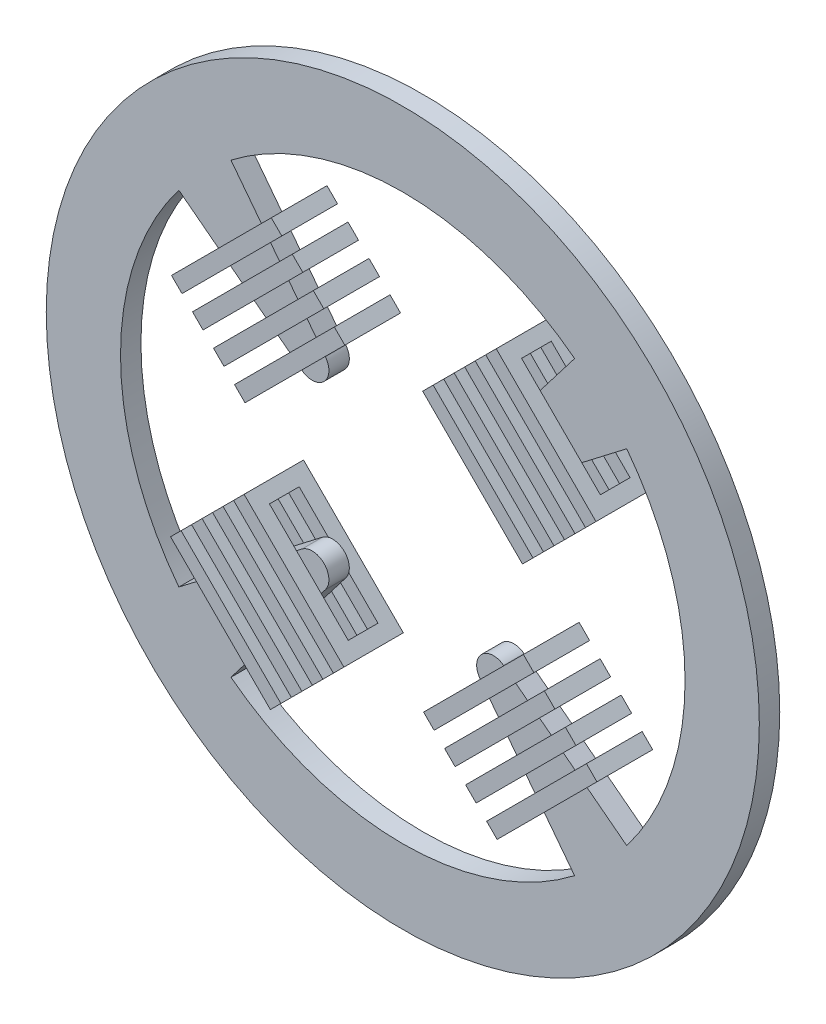
SolidWorks part; units mm, degrees
other "標示1"
sketch "草圖65"
ref_plane "前基準面" through (0, 0, 0) normal (0, 0, 1) x (1, 0, 0)
ref_plane "上基準面" through (0, 0, 0) normal (0, 1, 0) x (1, 0, 0)
ref_plane "右基準面" through (0, 0, 0) normal (1, 0, 0) x (0, 0, -1)
sketch "草圖1" plane through (0, 0, 0) normal (0, 0, 1) x (1, 0, 0)
  circle A0 centre (0, 0) radius 0.96
  circle A1 centre (0, 0) radius 0.76
extrude "填料-伸長1" add sketch "草圖1" along normal blind 0.055
sketch "草圖2" plane through (0, 0, 0.055) normal (0, 0, 1) x (1, 0, 0)
  line L0 (0, 0) -> (0, 1.565) construction
  line L1 (0, 0) -> (-1.8584, 0) construction
  line L2 (-0.0447, 0.3392) -> (-0.0992, 0.7535)
  line L3 (0.0447, 0.3392) -> (0.0992, 0.7535)
  line L4 (0.2714, 0.2082) -> (0.6029, 0.4627)
  line L5 (0.2082, 0.2714) -> (0.4627, 0.6029)
  line L6 (0.2082, -0.2714) -> (0.4627, -0.6029)
  line L7 (0.2714, -0.2082) -> (0.6029, -0.4627)
  line L8 (-0.2714, -0.2082) -> (-0.6029, -0.4627)
  line L9 (-0.2082, -0.2714) -> (-0.4627, -0.6029)
  line L10 (-0.2082, 0.2714) -> (-0.4627, 0.6029)
  line L11 (-0.2714, 0.2082) -> (-0.6029, 0.4627)
  circle A0 centre (0, 0) radius 0.3
  circle A1 centre (0, 0) radius 0.76 construction
  arc A3 (-0.0447, 0.3392) -> (0.0447, 0.3392) centre (0, 0.345) ccw
  arc A4 (0.0992, 0.7535) -> (-0.0992, 0.7535) centre (0, 0) ccw
  arc A5 (-0.76, 0) -> (0.76, 0) centre (0, 0) ccw
  arc A6 (0.6029, 0.4627) -> (0.4627, 0.6029) centre (0, 0) ccw
  arc A7 (0.2082, 0.2714) -> (0.2714, 0.2082) centre (0.244, 0.244) ccw
  arc A8 (0.4627, -0.6029) -> (0.6029, -0.4627) centre (0, 0) ccw
  arc A9 (0.2714, -0.2082) -> (0.2082, -0.2714) centre (0.244, -0.244) ccw
  arc A10 (-0.6029, -0.4627) -> (-0.4627, -0.6029) centre (0, 0) ccw
  arc A11 (-0.2082, -0.2714) -> (-0.2714, -0.2082) centre (-0.244, -0.244) ccw
  arc A12 (-0.4627, 0.6029) -> (-0.6029, 0.4627) centre (0, 0) ccw
  arc A13 (-0.2714, 0.2082) -> (-0.2082, 0.2714) centre (-0.244, 0.244) ccw
  point P23 (0, 0)
  point P34 (0, 0)
  point P41 (0, 0)
  circle M4 centre (0, 0) radius 0.76
  dimension "D1" = 7.5
  dimension "D3" = 2
  dimension "D4" = 4
  dimension "D2" = 7.5
extrude "填料-伸長2" add sketch "草圖2" against normal blind 0.055 contours L11 A13 L10 M4 | L5 A7 L4 M4 | L7 A9 L6 M4 | A11 L8 L9 M4
sketch "草圖7" plane through (0, 0, 0.055) normal (0, 0, 1) x (1, 0, 0)
  line L0 (0.2121, 0.2121) -> (0.2404, 0.2404) construction
  line L1 (0.2404, 0.2404) -> (0.2013, 0.2795) construction
  line L2 (0.2404, 0.2404) -> (0.5894, 0.5894) construction
  line L3 (0.0244, -0.0244) -> (-0.6648, 0.6648) construction
  line L4 (0.2404, -0.2404) -> (0.3328, -0.148)
  arc A0 (0.2082, 0.2714) -> (0.2714, 0.2082) centre (0.244, 0.244) ccw construction
  arc A1 (-0.2082, -0.2714) -> (-0.2714, -0.2082) centre (-0.244, -0.244) ccw construction
  arc A2 (-0.2714, 0.2082) -> (-0.2082, 0.2714) centre (-0.244, 0.244) ccw construction
  arc A3 (0.2714, -0.2082) -> (0.2082, -0.2714) centre (0.244, -0.244) ccw construction
  point P5 (0.297, 0.297)
  point P7 (-0.2121, -0.2121)
  point P8 (0.3536, 0.3536)
  point P9 (0.4101, 0.4101)
  point P12 (-0.2404, -0.2404)
  point P16 (-0.297, -0.297)
  point P17 (-0.3536, -0.3536)
  point P18 (-0.4101, -0.4101)
  point P20 (0.2404, -0.2404)
  point P23 (-0.2404, 0.2404)
  point P24 (-0.2121, 0.2121)
  point P25 (0.2121, -0.2121)
  point P29 (0.297, -0.297)
  point P33 (0.3536, -0.3536)
  point P34 (0.4101, -0.4101)
  point P35 (-0.297, 0.297)
  point P36 (-0.3536, 0.3536)
  point P37 (-0.4101, 0.4101)
  point P40 (0.4667, -0.4667)
  point P41 (0.5233, -0.5233)
  point P42 (0.4667, 0.4667)
  point P43 (0.5233, 0.5233)
  point P44 (-0.4667, 0.4667)
  point P45 (-0.5233, 0.5233)
  point P46 (-0.4667, -0.4667)
  point P47 (-0.5233, -0.5233)
  point P48 (0, 0)
  dimension "D1" = 0.08
  dimension "D2" = 0.08
  dimension "D3" = 0.08
  dimension "D4" = 0.04
  dimension "D5" = 0.04
  dimension "D6" = 0.08
  dimension "D7" = 0.08
  dimension "D8" = 0.08
  dimension "D9" = 0.04
  dimension "D10" = 0.04
  dimension "D11" = 0.08
  dimension "D12" = 0.08
  dimension "D13" = 0.08
  dimension "D14" = 0.08
  dimension "D15" = 0.08
  dimension "D16" = 0.08
  dimension "D17" = 0.08
  dimension "D18" = 0.08
  dimension "D19" = 0.08
  dimension "D20" = 0.08
  dimension "D21" = 0.08
  dimension "D22" = 0.08
  dimension "D23" = 0.08
  dimension "D24" = 0.08
ref_plane "平面5" through (0.2404, 0.2404, 0) normal (0.7071, 0.7071, 0) x (-0.7071, 0.7071, 0)
sketch "草圖11" plane through (0.2404, 0.2404, 0) normal (0.7071, 0.7071, 0) x (-0.7071, 0.7071, 0)
  line L0 (0, 0.055) -> (0, 0.1261) construction
  line L1 (-0.15, 0.0675) -> (0.15, 0.0675)
  line L2 (0.19, 0.1075) -> (-0.19, 0.1075)
  line L7 (-0.19, -0.0525) -> (0.19, -0.0525)
  line L17 (0.19, 0.1075) -> (0.19, -0.0525)
  line L18 (-0.19, 0.1075) -> (-0.19, -0.0525)
  line L19 (-0.15, -0.0125) -> (0.15, -0.0125)
  line L20 (-0.15, 0.0675) -> (-0.15, -0.0125)
  line L21 (0.15, 0.0675) -> (0.15, -0.0125)
  point P1 (0, 0.0275)
  point P2 (0, -0.0125)
  point P9 (0, 0.055)
  point P10 (0, -0.0525)
  point P11 (0, 0)
  point P13 (0, 0.1075)
  point P16 (0, -0.0525)
  point P19 (0, 0.0675)
  point P21 (0, 0.0675)
  point P22 (0, 0.1075)
  point P24 (0, -0.0125)
  dimension "D1" = 0.04
  dimension "D2" = 0.04
  dimension "D3" = 0.38
  dimension "D4" = 0.04
  dimension "D7" = 0.04
extrude "填料-伸長3" add sketch "草圖11" along normal blind 0.04 separate body
ref_plane "平面6" through (0.297, 0.297, 0) normal (0.7071, 0.7071, 0) x (0.7071, -0.7071, 0)
ref_plane "平面7" through (0.3536, 0.3536, 0) normal (0.7071, 0.7071, 0) x (0.7071, -0.7071, 0)
ref_plane "平面8" through (0.4101, 0.4101, 0) normal (0.7071, 0.7071, 0) x (0.7071, -0.7071, 0)
ref_plane "平面9" through (-0.2404, -0.2404, 0) normal (0.7071, 0.7071, 0) x (0.7071, -0.7071, 0)
ref_plane "平面10" through (-0.297, -0.297, 0) normal (0.7071, 0.7071, 0) x (0.7071, -0.7071, 0)
ref_plane "平面11" through (-0.3536, -0.3536, 0) normal (0.7071, 0.7071, 0) x (0.7071, -0.7071, 0)
ref_plane "平面12" through (-0.4101, -0.4101, 0) normal (0.7071, 0.7071, 0) x (0.7071, -0.7071, 0)
ref_plane "平面13" through (0.2404, -0.2404, 0) normal (0.7071, -0.7071, 0) x (0.7071, 0.7071, 0)
ref_plane "平面14" through (0.297, -0.297, 0) normal (0.7071, -0.7071, 0) x (0, 0, -1)
ref_plane "平面15" through (0.3536, -0.3536, 0) normal (0.7071, -0.7071, 0) x (0, 0, -1)
ref_plane "平面16" through (0.4101, -0.4101, 0) normal (0.7071, -0.7071, 0) x (0, 0, -1)
ref_plane "平面17" through (-0.2404, 0.2404, 0) normal (0.7071, -0.7071, 0) x (0, 0, -1)
ref_plane "平面18" through (-0.297, 0.297, 0) normal (0.7071, -0.7071, 0) x (0, 0, -1)
ref_plane "平面19" through (-0.3536, 0.3536, 0) normal (0.7071, -0.7071, 0) x (0, 0, -1)
ref_plane "平面20" through (-0.4101, 0.4101, 0) normal (0.7071, -0.7071, 0) x (0, 0, -1)
sketch "草圖60" plane through (0.2404, -0.2404, 0) normal (0.7071, -0.7071, 0) x (0.7071, 0.7071, 0)
sketch "草圖62" plane through (0.2404, -0.2404, 0) normal (0.7071, -0.7071, 0) x (0.7071, 0.7071, 0)
  line L0 (0, -0.0586) -> (0, 0.1686)
  line L2 (0.15, 0.065) -> (-0.15, 0.065)
  line L3 (-0.15, 0.065) -> (-0.15, -0.005)
  line L4 (-0.15, -0.005) -> (0.15, -0.005)
  line L5 (0.15, -0.005) -> (0.15, 0.065)
  line L6 (0.19, 0.105) -> (-0.19, 0.105)
  line L7 (-0.19, 0.105) -> (-0.19, -0.045)
  line L8 (-0.19, -0.045) -> (0.19, -0.045)
  line L9 (0.19, -0.045) -> (0.19, 0.105)
  point P0 (0, 0.065)
  point P4 (0, 0.055)
  point P5 (0, -0.005)
  point P8 (0, 0.105)
  point P11 (0, 0.065)
  point P14 (0, -0.045)
  point P18 (0, 0.105)
  dimension "D1" = 0.01
  dimension "D2" = 0.06
  dimension "D3" = 0.04
  dimension "D4" = 0.04
  dimension "D5" = 0.38
  dimension "D6" = 0.3
sketch "草圖64" plane through (0.297, -0.297, 0) normal (0.7071, -0.7071, 0) x (0, 0, -1)
  line L0 (0.045, 0.19) -> (-0.105, 0.19) construction
  line L1 (0.005, 0.15) -> (-0.065, 0.15) construction
  line L2 (0.045, -0.19) -> (0.045, 0.19) construction
  line L3 (0.005, -0.15) -> (0.005, 0.15) construction
  line L4 (-0.065, -0.15) -> (0.005, -0.15) construction
  line L5 (-0.065, 0.15) -> (-0.065, -0.15) construction
  line L6 (-0.105, -0.19) -> (0.045, -0.19) construction
  line L7 (-0.105, 0.19) -> (-0.105, -0.19) construction
  line L8 (0.045, 0.19) -> (-0.105, 0.19)
  line L9 (0.005, 0.15) -> (-0.065, 0.15)
  line L10 (0.045, -0.19) -> (0.045, 0.19)
  line L11 (0.005, -0.15) -> (0.005, 0.15)
  line L12 (-0.065, -0.15) -> (0.005, -0.15)
  line L13 (-0.065, 0.15) -> (-0.065, -0.15)
  line L14 (-0.105, -0.19) -> (0.045, -0.19)
  line L15 (-0.105, 0.19) -> (-0.105, -0.19)
sketch "草圖68" plane through (0.3536, -0.3536, 0) normal (0.7071, -0.7071, 0) x (0, 0, -1)
  line L0 (-0.105, -0.19) -> (0.045, -0.19) construction
  line L1 (-0.065, -0.15) -> (0.005, -0.15) construction
  line L2 (0.005, -0.15) -> (0.005, 0.15) construction
  line L3 (-0.065, 0.15) -> (-0.065, -0.15) construction
  line L4 (0.005, 0.15) -> (-0.065, 0.15) construction
  line L5 (0.045, -0.19) -> (0.045, 0.19) construction
  line L6 (0.045, 0.19) -> (-0.105, 0.19) construction
  line L7 (-0.105, 0.19) -> (-0.105, -0.19) construction
  line L8 (-0.105, -0.19) -> (0.045, -0.19)
  line L9 (-0.065, -0.15) -> (0.005, -0.15)
  line L10 (0.005, -0.15) -> (0.005, 0.15)
  line L11 (-0.065, 0.15) -> (-0.065, -0.15)
  line L12 (0.005, 0.15) -> (-0.065, 0.15)
  line L13 (0.045, -0.19) -> (0.045, 0.19)
  line L14 (0.045, 0.19) -> (-0.105, 0.19)
  line L15 (-0.105, 0.19) -> (-0.105, -0.19)
sketch "草圖69" plane through (0.4101, -0.4101, 0) normal (0.7071, -0.7071, 0) x (0, 0, -1)
  line L0 (0.045, -0.19) -> (0.045, 0.19) construction
  line L1 (0.045, 0.19) -> (-0.105, 0.19) construction
  line L2 (-0.105, 0.19) -> (-0.105, -0.19) construction
  line L3 (-0.105, -0.19) -> (0.045, -0.19) construction
  line L4 (-0.065, -0.15) -> (0.005, -0.15) construction
  line L5 (0.005, -0.15) -> (0.005, 0.15) construction
  line L6 (-0.065, 0.15) -> (-0.065, -0.15) construction
  line L7 (0.005, 0.15) -> (-0.065, 0.15) construction
  line L8 (0.045, -0.19) -> (0.045, 0.19)
  line L9 (0.045, 0.19) -> (-0.105, 0.19)
  line L10 (-0.105, 0.19) -> (-0.105, -0.19)
  line L11 (-0.105, -0.19) -> (0.045, -0.19)
  line L12 (-0.065, -0.15) -> (0.005, -0.15)
  line L13 (0.005, -0.15) -> (0.005, 0.15)
  line L14 (-0.065, 0.15) -> (-0.065, -0.15)
  line L15 (0.005, 0.15) -> (-0.065, 0.15)
sketch "草圖70" plane through (-0.2404, 0.2404, 0) normal (0.7071, -0.7071, 0) x (0, 0, -1)
  line L0 (-0.105, 0.19) -> (-0.105, -0.19) construction
  line L1 (-0.105, -0.19) -> (0.045, -0.19) construction
  line L2 (-0.065, -0.15) -> (0.005, -0.15) construction
  line L3 (-0.065, 0.15) -> (-0.065, -0.15) construction
  line L4 (0.005, -0.15) -> (0.005, 0.15) construction
  line L5 (0.005, 0.15) -> (-0.065, 0.15) construction
  line L6 (0.045, -0.19) -> (0.045, 0.19) construction
  line L7 (0.045, 0.19) -> (-0.105, 0.19) construction
  line L8 (-0.105, 0.19) -> (-0.105, -0.19)
  line L9 (-0.105, -0.19) -> (0.045, -0.19)
  line L10 (-0.065, -0.15) -> (0.005, -0.15)
  line L11 (-0.065, 0.15) -> (-0.065, -0.15)
  line L12 (0.005, -0.15) -> (0.005, 0.15)
  line L13 (0.005, 0.15) -> (-0.065, 0.15)
  line L14 (0.045, -0.19) -> (0.045, 0.19)
  line L15 (0.045, 0.19) -> (-0.105, 0.19)
sketch "草圖71" plane through (-0.297, 0.297, 0) normal (0.7071, -0.7071, 0) x (0, 0, -1)
  line L0 (0.045, -0.19) -> (0.045, 0.19) construction
  line L1 (-0.105, -0.19) -> (0.045, -0.19) construction
  line L2 (-0.065, -0.15) -> (0.005, -0.15) construction
  line L3 (0.005, -0.15) -> (0.005, 0.15) construction
  line L4 (-0.065, 0.15) -> (-0.065, -0.15) construction
  line L5 (0.005, 0.15) -> (-0.065, 0.15) construction
  line L6 (-0.105, 0.19) -> (-0.105, -0.19) construction
  line L7 (0.045, 0.19) -> (-0.105, 0.19) construction
  line L8 (0.045, -0.19) -> (0.045, 0.19)
  line L9 (-0.105, -0.19) -> (0.045, -0.19)
  line L10 (-0.065, -0.15) -> (0.005, -0.15)
  line L11 (0.005, -0.15) -> (0.005, 0.15)
  line L12 (-0.065, 0.15) -> (-0.065, -0.15)
  line L13 (0.005, 0.15) -> (-0.065, 0.15)
  line L14 (-0.105, 0.19) -> (-0.105, -0.19)
  line L15 (0.045, 0.19) -> (-0.105, 0.19)
sketch "草圖72" plane through (-0.3536, 0.3536, 0) normal (0.7071, -0.7071, 0) x (0, 0, -1)
  line L0 (-0.105, -0.19) -> (0.045, -0.19) construction
  line L1 (-0.105, 0.19) -> (-0.105, -0.19) construction
  line L2 (-0.065, 0.15) -> (-0.065, -0.15) construction
  line L3 (0.005, -0.15) -> (0.005, 0.15) construction
  line L4 (0.005, 0.15) -> (-0.065, 0.15) construction
  line L5 (0.045, 0.19) -> (-0.105, 0.19) construction
  line L6 (0.045, -0.19) -> (0.045, 0.19) construction
  line L7 (-0.105, -0.19) -> (0.045, -0.19)
  line L8 (-0.105, 0.19) -> (-0.105, -0.19)
  line L9 (-0.065, 0.15) -> (-0.065, -0.15)
  line L10 (0.005, -0.15) -> (0.005, 0.15)
  line L11 (0.005, 0.15) -> (-0.065, 0.15)
  line L12 (0.045, 0.19) -> (-0.105, 0.19)
  line L13 (0.045, -0.19) -> (0.045, 0.19)
  line L14 (-0.065, -0.15) -> (0.005, -0.15)
sketch "草圖73" plane through (-0.4101, 0.4101, 0) normal (0.7071, -0.7071, 0) x (0, 0, -1)
  line L0 (-0.065, -0.15) -> (0.005, -0.15) construction
  line L1 (-0.105, -0.19) -> (0.045, -0.19) construction
  line L2 (-0.105, 0.19) -> (-0.105, -0.19) construction
  line L3 (-0.065, 0.15) -> (-0.065, -0.15) construction
  line L4 (0.005, 0.15) -> (-0.065, 0.15) construction
  line L5 (0.005, -0.15) -> (0.005, 0.15) construction
  line L6 (0.045, -0.19) -> (0.045, 0.19) construction
  line L7 (0.045, 0.19) -> (-0.105, 0.19) construction
  line L8 (-0.065, -0.15) -> (0.005, -0.15)
  line L9 (-0.105, -0.19) -> (0.045, -0.19)
  line L10 (-0.105, 0.19) -> (-0.105, -0.19)
  line L11 (-0.065, 0.15) -> (-0.065, -0.15)
  line L12 (0.005, 0.15) -> (-0.065, 0.15)
  line L13 (0.005, -0.15) -> (0.005, 0.15)
  line L14 (0.045, -0.19) -> (0.045, 0.19)
  line L15 (0.045, 0.19) -> (-0.105, 0.19)
sketch "草圖74" plane through (-0.3536, 0.3536, 0) normal (0.7071, -0.7071, 0) x (0, 0, -1)
  line L0 (-0.065, -0.15) -> (0.005, -0.15) construction
  line L1 (-0.065, -0.15) -> (0.005, -0.15)
extrude "填料-伸長28" add sketch "草圖62" along normal blind 0.04 separate body contours L8 L9 L6 L0 L2 L5 L4 | L7 L8 L0 L4 L3 L2 L6
extrude "填料-伸長29" add sketch "草圖64" along normal blind 0.04 separate body
extrude "填料-伸長30" add sketch "草圖68" along normal blind 0.04 separate body
extrude "填料-伸長31" add sketch "草圖69" along normal blind 0.04 separate body
extrude "填料-伸長32" add sketch "草圖70" against normal blind 0.04 separate body
extrude "填料-伸長33" add sketch "草圖71" against normal blind 0.04 separate body
extrude "填料-伸長34" add sketch "草圖72" against normal blind 0.04 separate body
extrude "填料-伸長35" add sketch "草圖73" against normal blind 0.04 separate body
sketch "草圖76" plane through (0.297, 0.297, 0) normal (0.7071, 0.7071, 0) x (0.7071, -0.7071, 0)
  line L0 (0.19, -0.1075) -> (0.19, 0.0525) construction
  line L1 (0.15, -0.0675) -> (0.15, 0.0125) construction
  line L2 (-0.19, -0.1075) -> (0.19, -0.1075) construction
  line L3 (0.15, -0.0675) -> (-0.15, -0.0675) construction
  line L4 (-0.15, -0.0675) -> (-0.15, 0.0125) construction
  line L5 (-0.19, -0.1075) -> (-0.19, 0.0525) construction
  line L6 (0.19, 0.0525) -> (-0.19, 0.0525) construction
  line L7 (0.15, 0.0125) -> (-0.15, 0.0125) construction
  line L8 (0.19, -0.1075) -> (0.19, 0.0525)
  line L9 (0.15, -0.0675) -> (0.15, 0.0125)
  line L10 (-0.19, -0.1075) -> (0.19, -0.1075)
  line L11 (0.15, -0.0675) -> (-0.15, -0.0675)
  line L12 (-0.15, -0.0675) -> (-0.15, 0.0125)
  line L13 (-0.19, -0.1075) -> (-0.19, 0.0525)
  line L14 (0.19, 0.0525) -> (-0.19, 0.0525)
  line L15 (0.15, 0.0125) -> (-0.15, 0.0125)
sketch "草圖77" plane through (0.3536, 0.3536, 0) normal (0.7071, 0.7071, 0) x (0.7071, -0.7071, 0)
  line L0 (0.19, -0.1075) -> (0.19, 0.0525) construction
  line L1 (0.15, -0.0675) -> (0.15, 0.0125) construction
  line L2 (-0.19, -0.1075) -> (0.19, -0.1075) construction
  line L3 (0.15, -0.0675) -> (-0.15, -0.0675) construction
  line L4 (-0.15, -0.0675) -> (-0.15, 0.0125) construction
  line L5 (-0.19, -0.1075) -> (-0.19, 0.0525) construction
  line L6 (0.19, 0.0525) -> (-0.19, 0.0525) construction
  line L7 (0.15, 0.0125) -> (-0.15, 0.0125) construction
  line L8 (0.19, -0.1075) -> (0.19, 0.0525)
  line L9 (0.15, -0.0675) -> (0.15, 0.0125)
  line L10 (-0.19, -0.1075) -> (0.19, -0.1075)
  line L11 (0.15, -0.0675) -> (-0.15, -0.0675)
  line L12 (-0.15, -0.0675) -> (-0.15, 0.0125)
  line L13 (-0.19, -0.1075) -> (-0.19, 0.0525)
  line L14 (0.19, 0.0525) -> (-0.19, 0.0525)
  line L15 (0.15, 0.0125) -> (-0.15, 0.0125)
sketch "草圖78" plane through (0.4101, 0.4101, 0) normal (0.7071, 0.7071, 0) x (0.7071, -0.7071, 0)
  line L0 (0.19, -0.1075) -> (0.19, 0.0525) construction
  line L1 (-0.19, -0.1075) -> (0.19, -0.1075) construction
  line L2 (0.19, 0.0525) -> (-0.19, 0.0525) construction
  line L3 (-0.19, -0.1075) -> (-0.19, 0.0525) construction
  line L4 (0.15, -0.0675) -> (-0.15, -0.0675) construction
  line L5 (0.15, -0.0675) -> (0.15, 0.0125) construction
  line L6 (0.15, 0.0125) -> (-0.15, 0.0125) construction
  line L7 (-0.15, -0.0675) -> (-0.15, 0.0125) construction
  line L8 (0.19, -0.1075) -> (0.19, 0.0525)
  line L9 (-0.19, -0.1075) -> (0.19, -0.1075)
  line L10 (0.19, 0.0525) -> (-0.19, 0.0525)
  line L11 (-0.19, -0.1075) -> (-0.19, 0.0525)
  line L12 (0.15, -0.0675) -> (-0.15, -0.0675)
  line L13 (0.15, -0.0675) -> (0.15, 0.0125)
  line L14 (0.15, 0.0125) -> (-0.15, 0.0125)
  line L15 (-0.15, -0.0675) -> (-0.15, 0.0125)
sketch "草圖79" plane through (-0.2404, -0.2404, 0) normal (0.7071, 0.7071, 0) x (0.7071, -0.7071, 0)
  line L0 (-0.19, -0.1075) -> (0.19, -0.1075) construction
  line L1 (0.15, -0.0675) -> (-0.15, -0.0675) construction
  line L2 (-0.15, -0.0675) -> (-0.15, 0.0125) construction
  line L3 (-0.19, -0.1075) -> (-0.19, 0.0525) construction
  line L4 (0.19, -0.1075) -> (0.19, 0.0525) construction
  line L5 (0.15, -0.0675) -> (0.15, 0.0125) construction
  line L6 (0.15, 0.0125) -> (-0.15, 0.0125) construction
  line L7 (0.19, 0.0525) -> (-0.19, 0.0525) construction
  line L8 (-0.19, -0.1075) -> (0.19, -0.1075)
  line L9 (0.15, -0.0675) -> (-0.15, -0.0675)
  line L10 (-0.15, -0.0675) -> (-0.15, 0.0125)
  line L11 (-0.19, -0.1075) -> (-0.19, 0.0525)
  line L12 (0.19, -0.1075) -> (0.19, 0.0525)
  line L13 (0.15, -0.0675) -> (0.15, 0.0125)
  line L14 (0.15, 0.0125) -> (-0.15, 0.0125)
  line L15 (0.19, 0.0525) -> (-0.19, 0.0525)
sketch "草圖80" plane through (-0.297, -0.297, 0) normal (0.7071, 0.7071, 0) x (0.7071, -0.7071, 0)
  line L0 (-0.19, -0.1075) -> (0.19, -0.1075) construction
  line L1 (0.19, -0.1075) -> (0.19, 0.0525) construction
  line L2 (0.19, 0.0525) -> (-0.19, 0.0525) construction
  line L3 (-0.19, -0.1075) -> (-0.19, 0.0525) construction
  line L4 (-0.15, -0.0675) -> (-0.15, 0.0125) construction
  line L5 (0.15, -0.0675) -> (-0.15, -0.0675) construction
  line L6 (0.15, -0.0675) -> (0.15, 0.0125) construction
  line L7 (0.15, 0.0125) -> (-0.15, 0.0125) construction
  line L8 (-0.19, -0.1075) -> (0.19, -0.1075)
  line L9 (0.19, -0.1075) -> (0.19, 0.0525)
  line L10 (0.19, 0.0525) -> (-0.19, 0.0525)
  line L11 (-0.19, -0.1075) -> (-0.19, 0.0525)
  line L12 (-0.15, -0.0675) -> (-0.15, 0.0125)
  line L13 (0.15, -0.0675) -> (-0.15, -0.0675)
  line L14 (0.15, -0.0675) -> (0.15, 0.0125)
  line L15 (0.15, 0.0125) -> (-0.15, 0.0125)
sketch "草圖81" plane through (-0.3536, -0.3536, 0) normal (0.7071, 0.7071, 0) x (0.7071, -0.7071, 0)
  line L0 (-0.19, -0.1075) -> (0.19, -0.1075) construction
  line L1 (0.19, -0.1075) -> (0.19, 0.0525) construction
  line L2 (0.19, 0.0525) -> (-0.19, 0.0525) construction
  line L3 (-0.19, -0.1075) -> (-0.19, 0.0525) construction
  line L4 (-0.15, -0.0675) -> (-0.15, 0.0125) construction
  line L5 (0.15, -0.0675) -> (-0.15, -0.0675) construction
  line L6 (0.15, -0.0675) -> (0.15, 0.0125) construction
  line L7 (0.15, 0.0125) -> (-0.15, 0.0125) construction
  line L8 (-0.19, -0.1075) -> (0.19, -0.1075)
  line L9 (0.19, -0.1075) -> (0.19, 0.0525)
  line L10 (0.19, 0.0525) -> (-0.19, 0.0525)
  line L11 (-0.19, -0.1075) -> (-0.19, 0.0525)
  line L12 (-0.15, -0.0675) -> (-0.15, 0.0125)
  line L13 (0.15, -0.0675) -> (-0.15, -0.0675)
  line L14 (0.15, -0.0675) -> (0.15, 0.0125)
  line L15 (0.15, 0.0125) -> (-0.15, 0.0125)
sketch "草圖82" plane through (-0.4101, -0.4101, 0) normal (0.7071, 0.7071, 0) x (0.7071, -0.7071, 0)
  line L0 (0.19, -0.1075) -> (0.19, 0.0525) construction
  line L1 (-0.19, -0.1075) -> (0.19, -0.1075) construction
  line L2 (-0.15, -0.0675) -> (-0.15, 0.0125) construction
  line L3 (0.15, -0.0675) -> (-0.15, -0.0675) construction
  line L4 (0.15, -0.0675) -> (0.15, 0.0125) construction
  line L5 (0.15, 0.0125) -> (-0.15, 0.0125) construction
  line L6 (0.19, 0.0525) -> (-0.19, 0.0525) construction
  line L7 (-0.19, -0.1075) -> (-0.19, 0.0525) construction
  line L8 (0.19, -0.1075) -> (0.19, 0.0525)
  line L9 (-0.19, -0.1075) -> (0.19, -0.1075)
  line L10 (-0.15, -0.0675) -> (-0.15, 0.0125)
  line L11 (0.15, -0.0675) -> (-0.15, -0.0675)
  line L12 (0.15, -0.0675) -> (0.15, 0.0125)
  line L13 (0.15, 0.0125) -> (-0.15, 0.0125)
  line L14 (0.19, 0.0525) -> (-0.19, 0.0525)
  line L15 (-0.19, -0.1075) -> (-0.19, 0.0525)
extrude "填料-伸長36" add sketch "草圖76" along normal blind 0.04 separate body
extrude "填料-伸長37" add sketch "草圖77" along normal blind 0.04 separate body
extrude "填料-伸長38" add sketch "草圖78" along normal blind 0.04 separate body
extrude "填料-伸長39" add sketch "草圖79" against normal blind 0.04 separate body
extrude "填料-伸長40" add sketch "草圖80" against normal blind 0.04 separate body
extrude "填料-伸長41" add sketch "草圖81" against normal blind 0.04 separate body
extrude "填料-伸長42" add sketch "草圖82" against normal blind 0.04 separate body
